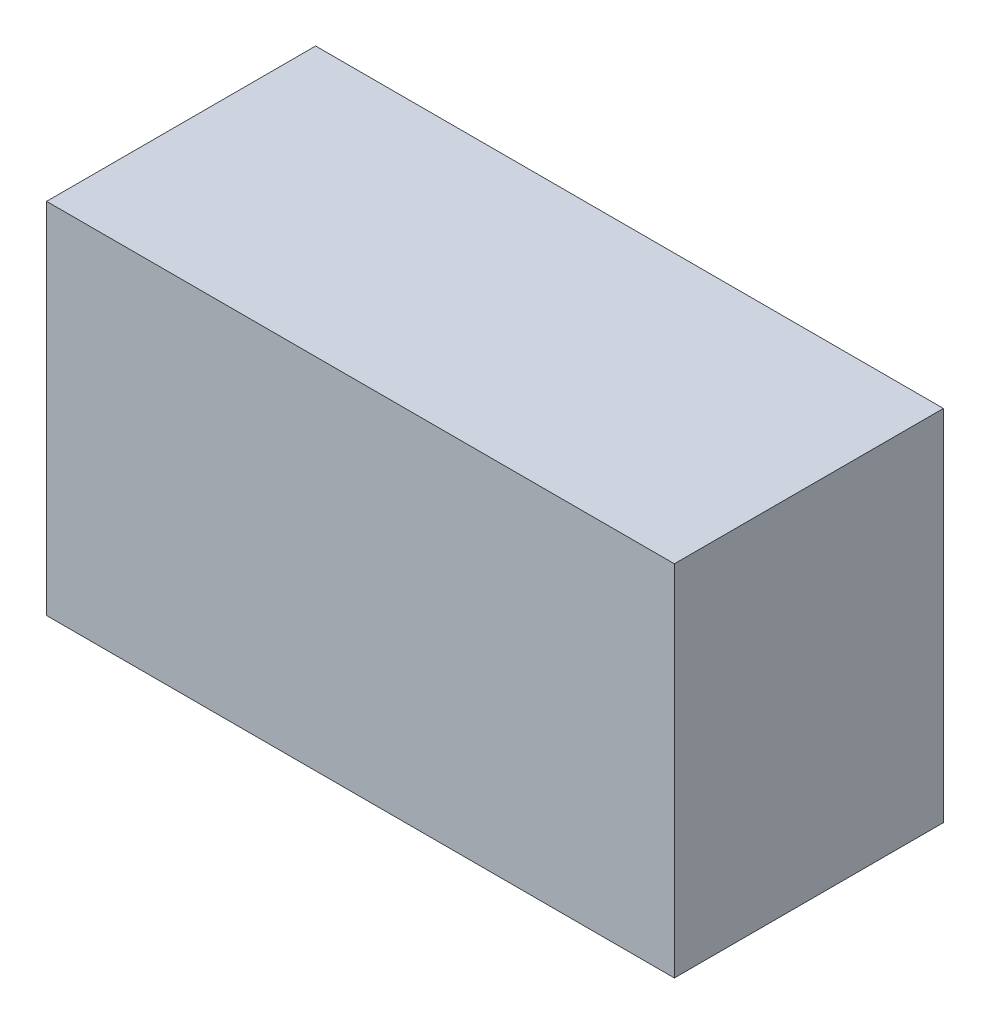
SolidWorks part; units mm, degrees
ref_plane "正面" through (0, 0, 0) normal (0, 0, 1) x (1, 0, 0)
ref_plane "平面" through (0, 0, 0) normal (0, 1, 0) x (1, 0, 0)
ref_plane "右側面" through (0, 0, 0) normal (1, 0, 0) x (0, 0, -1)
sketch "ｽｹｯﾁ1" plane through (0, 0, 0) normal (0, 0, 1) x (1, 0, 0)
  line L1 (0, 0) -> (7, 0)
  line L2 (0, 0) -> (0, 4)
  line L3 (0, 4) -> (7, 4)
  line L4 (7, 0) -> (7, 4)
  dimension "D1" = 4
  dimension "D2" = 7
extrude "ﾎﾞｽ - 押し出し1" add sketch "ｽｹｯﾁ1" along normal blind 3
